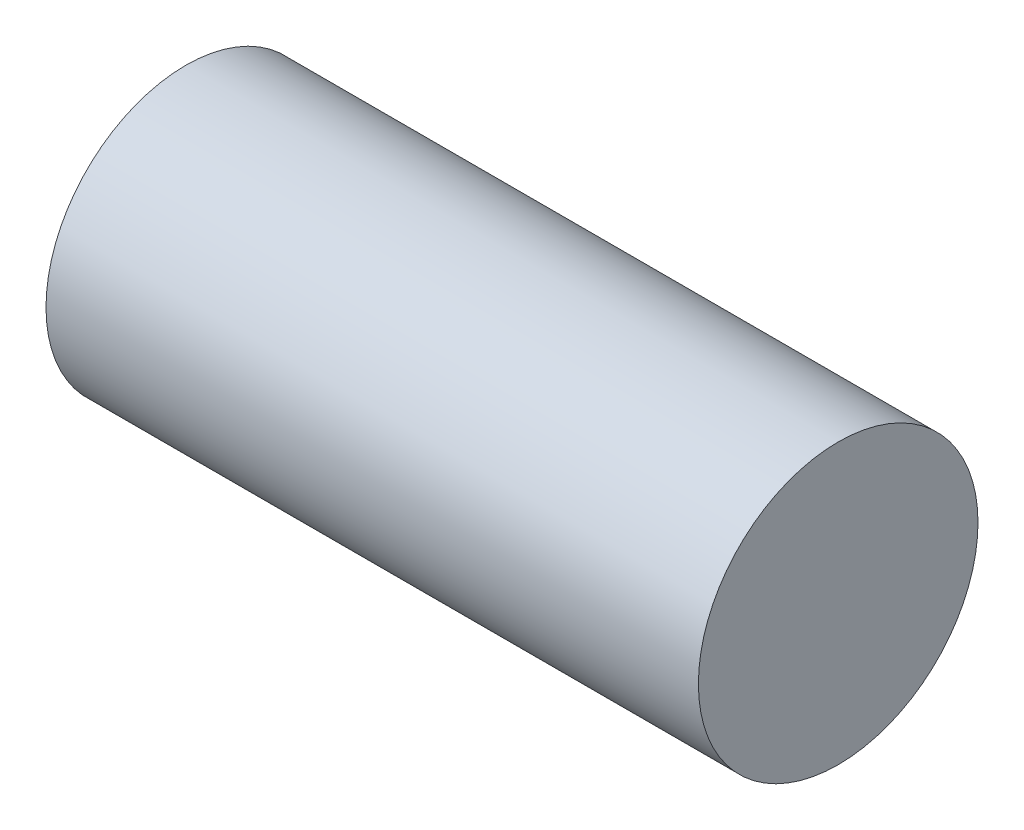
SolidWorks part; units mm, degrees
ref_plane "前视基准面" through (0, 0, 0) normal (0, 0, 1) x (1, 0, 0)
ref_plane "上视基准面" through (0, 0, 0) normal (0, 1, 0) x (1, 0, 0)
ref_plane "右视基准面" through (0, 0, 0) normal (1, 0, 0) x (0, 0, -1)
sketch "草图1" plane through (0, 0, 0) normal (1, 0, 0) x (0, 0, -1)
  circle A0 centre (0, 0) radius 1.5
extrude "凸台-拉伸1" add sketch "草图1" along normal blind 7
